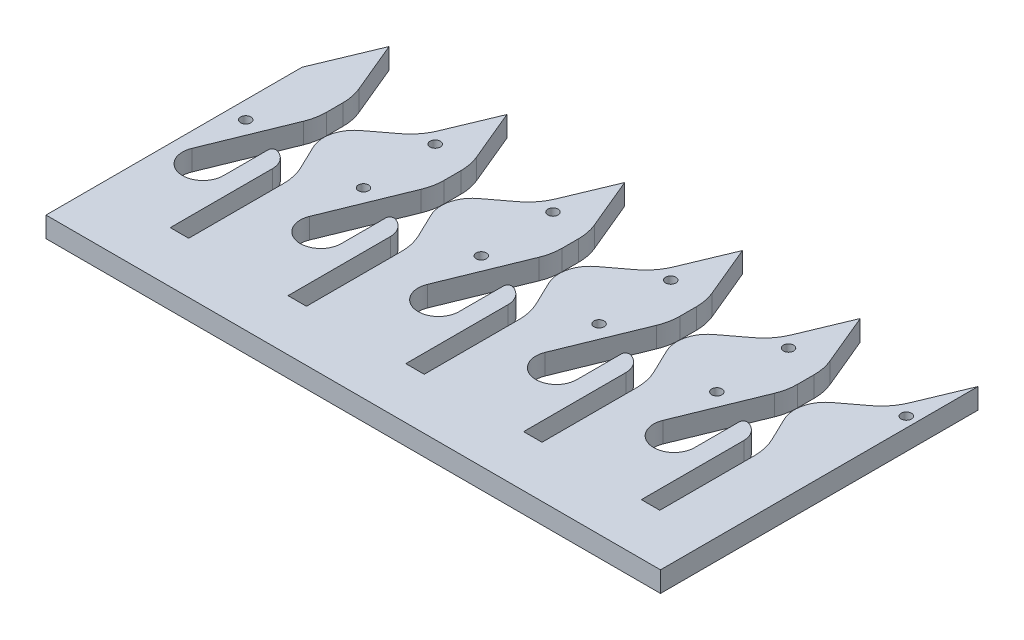
SolidWorks part; units mm, degrees
material "ABS"
ref_plane "Front Plane" through (0, 0, 0) normal (0, 0, 1) x (1, 0, 0)
ref_plane "Top Plane" through (0, 0, 0) normal (0, 1, 0) x (1, 0, 0)
ref_plane "Right Plane" through (0, 0, 0) normal (1, 0, 0) x (0, 0, -1)
sketch "Sketch1" plane through (0, 0, 0) normal (0, 1, 0) x (1, 0, 0)
  line L0 (-371.2073, 45) -> (137.2591, 45) construction
  line L1 (-371.2073, 155) -> (137.2591, 155) construction
  line L2 (-371.2073, 125) -> (137.2591, 125) construction
  line L5 (-371.2073, 25) -> (137.2591, 25) construction
  line L44 (137.2591, 0) -> (-371.2073, 0) construction
  line L45 (0, 0) -> (0, 226.1062) construction
  line L46 (-12.5, -27.5698) -> (-12.5, 226.1062) construction
  line L103 (0, 0) -> (-300, 0)
  line L105 (0, 0) -> (0, 155)
  line L106 (0, 155) -> (-12.5, 125)
  line L107 (-12.5, 125) -> (-29.0578, 112.4565)
  line L110 (-57.5, 155) -> (-45, 125)
  line L111 (-34.3445, 25) -> (-34.3445, 75)
  line L112 (-43.3445, 84) -> (-43.3445, 60)
  line L113 (-57.5, 233.627) -> (-57.5, -20.049) construction
  line L114 (-45, 125) -> (-45, 107)
  line L115 (-45, 107) -> (-62.6059, 63.7719)
  line L117 (-34.3445, 25) -> (-25.3445, 25)
  line L118 (-25.3445, 25) -> (-25.3445, 77)
  line L119 (-25.3445, 77) -> (-33.5185, 94)
  line L120 (-57.5, 155) -> (-70, 125)
  line L121 (-70, 125) -> (-86.5578, 112.4565)
  line L122 (-82.8445, 77) -> (-91.0185, 94)
  line L123 (-82.8445, 25) -> (-82.8445, 77)
  line L124 (-91.8445, 25) -> (-82.8445, 25)
  line L125 (-91.8445, 25) -> (-91.8445, 75)
  line L126 (-100.8445, 84) -> (-100.8445, 60)
  line L127 (-102.5, 107) -> (-120.1059, 63.7719)
  line L128 (-102.5, 125) -> (-102.5, 107)
  line L129 (-115, 155) -> (-102.5, 125)
  line L130 (-115, 155) -> (-127.5, 125)
  line L131 (-127.5, 125) -> (-144.0578, 112.4565)
  line L132 (-140.3445, 77) -> (-148.5185, 94)
  line L133 (-140.3445, 25) -> (-140.3445, 77)
  line L134 (-149.3445, 25) -> (-140.3445, 25)
  line L135 (-149.3445, 25) -> (-149.3445, 75)
  line L136 (-158.3445, 84) -> (-158.3445, 60)
  line L137 (-160, 107) -> (-177.6059, 63.7719)
  line L138 (-160, 125) -> (-160, 107)
  line L139 (-172.5, 155) -> (-160, 125)
  line L140 (-172.5, 155) -> (-185, 125)
  line L141 (-185, 125) -> (-201.5578, 112.4565)
  line L142 (-197.8445, 77) -> (-206.0185, 94)
  line L143 (-197.8445, 25) -> (-197.8445, 77)
  line L144 (-206.8445, 25) -> (-197.8445, 25)
  line L145 (-206.8445, 25) -> (-206.8445, 75)
  line L146 (-215.8445, 84) -> (-215.8445, 60)
  line L147 (-217.5, 107) -> (-235.1059, 63.7719)
  line L148 (-217.5, 125) -> (-217.5, 107)
  line L149 (-230, 155) -> (-217.5, 125)
  line L150 (-230, 155) -> (-242.5, 125)
  line L151 (-242.5, 125) -> (-259.0578, 112.4565)
  line L152 (-255.3445, 77) -> (-263.5185, 94)
  line L153 (-255.3445, 25) -> (-255.3445, 77)
  line L154 (-264.3445, 25) -> (-255.3445, 25)
  line L155 (-264.3445, 25) -> (-264.3445, 75)
  line L156 (-273.3445, 84) -> (-273.3445, 60)
  line L157 (-275, 107) -> (-292.6059, 63.7719)
  line L158 (-275, 125) -> (-275, 107)
  line L159 (-287.5, 155) -> (-275, 125)
  line L160 (-287.5, 155) -> (-300, 125)
  line L170 (-300, 0) -> (-300, 125)
  line L172 (-300, 125) -> (-316.5578, 112.4565) [skipped]
  line L173 (-312.8445, 77) -> (-321.0185, 94) [skipped]
  line L174 (-312.8445, 25) -> (-312.8445, 77) [skipped]
  line L175 (-321.8445, 25) -> (-321.8445, 75) [skipped]
  line L176 (-330.8445, 84) -> (-330.8445, 60) [skipped]
  line L177 (-332.5, 107) -> (-350.1059, 63.7719) [skipped]
  line L178 (-332.5, 125) -> (-332.5, 107) [skipped]
  line L179 (-321.8445, 25) -> (-312.8445, 25) [skipped]
  line L180 (-345, 155) -> (-332.5, 125) [skipped]
  arc A0 (-29.0578, 112.4565) -> (-33.5185, 94) centre (-20, 100.5) ccw
  arc A1 (-34.3445, 75) -> (-43.3445, 84) centre (-43.3445, 75) ccw
  arc A2 (-62.6059, 63.7719) -> (-43.3445, 60) centre (-53.3445, 60) ccw
  arc A3 (-86.5578, 112.4565) -> (-91.0185, 94) centre (-77.5, 100.5) ccw
  arc A4 (-91.8445, 75) -> (-100.8445, 84) centre (-100.8445, 75) ccw
  arc A5 (-120.1059, 63.7719) -> (-100.8445, 60) centre (-110.8445, 60) ccw
  arc A6 (-144.0578, 112.4565) -> (-148.5185, 94) centre (-135, 100.5) ccw
  arc A7 (-149.3445, 75) -> (-158.3445, 84) centre (-158.3445, 75) ccw
  arc A8 (-177.6059, 63.7719) -> (-158.3445, 60) centre (-168.3445, 60) ccw
  arc A9 (-201.5578, 112.4565) -> (-206.0185, 94) centre (-192.5, 100.5) ccw
  arc A10 (-206.8445, 75) -> (-215.8445, 84) centre (-215.8445, 75) ccw
  arc A11 (-235.1059, 63.7719) -> (-215.8445, 60) centre (-225.8445, 60) ccw
  arc A12 (-259.0578, 112.4565) -> (-263.5185, 94) centre (-250, 100.5) ccw
  arc A13 (-264.3445, 75) -> (-273.3445, 84) centre (-273.3445, 75) ccw
  arc A14 (-292.6059, 63.7719) -> (-273.3445, 60) centre (-283.3445, 60) ccw
  arc A18 (-316.5578, 112.4565) -> (-321.0185, 94) centre (-307.5, 100.5) ccw [skipped]
  arc A19 (-321.8445, 75) -> (-330.8445, 84) centre (-330.8445, 75) ccw [skipped]
  arc A20 (-350.1059, 63.7719) -> (-330.8445, 60) centre (-340.8445, 60) ccw [skipped]
  circle A21 centre (-5, 125) radius 2.5
  circle A22 centre (-61.5, 89) radius 2.5
  circle A23 centre (-62.5, 125) radius 2.5
  circle A24 centre (-119, 89) radius 2.5
  circle A25 centre (-120, 125) radius 2.5
  circle A26 centre (-176.5, 89) radius 2.5
  circle A27 centre (-177.5, 125) radius 2.5
  circle A28 centre (-234, 89) radius 2.5
  circle A29 centre (-235, 125) radius 2.5
  circle A30 centre (-291.5, 89) radius 2.5
  point P71 (0, 0)
  point P88 (0, 0)
  point P121 (-60.8516, 94)
  dimension "D7" = 30
  dimension "D8" = 24.5
  dimension "D9" = 20
  dimension "D12" = 9
  dimension "D13" = 57.5
  dimension "D18" = 17
  dimension "D16" = 10
  dimension "D21" = 6
  dimension "D20" = 5
  dimension "D23" = 5
  dimension "D2" = 25
  dimension "D3" = 20
  dimension "D4" = 80
  dimension "D5" = 30
  dimension "D6" = 12.5
  dimension "D10" = 9
  dimension "D11" = 52
  dimension "D14" = 15
  dimension "D15" = 300
  dimension "D17" = 50
  dimension "D19" = 18
  dimension "D22" = 5
  dimension "D24" = 36
  dimension "D26" = 4
  dimension "D25" = 5
extrude "Boss-Extrude1" add sketch "Sketch1" along normal blind 10
fillet "Fillet1" radius 25 20 edges at (-45, 5, -125) (-45, 5, -107) (-12.5, 5, -125) (-275, 5, -107) (-217.5, 5, -107) (-160, 5, -107) (-102.5, 5, -107) (-102.5, 5, -125) (-160, 5, -125) (-217.5, 5, -125) (-275, 5, -125) (-242.5, 5, -125) (-185, 5, -125) (-127.5, 5, -125) (-70, 5, -125) (-25.3445, 5, -77) (-82.8445, 5, -77) (-140.3445, 5, -77) (-197.8445, 5, -77) (-255.3445, 5, -77)
fillet "Fillet2" radius 2 5 edges at (-43.3445, 5, -84) (-273.3445, 5, -84) (-215.8445, 5, -84) (-158.3445, 5, -84) (-100.8445, 5, -84)
